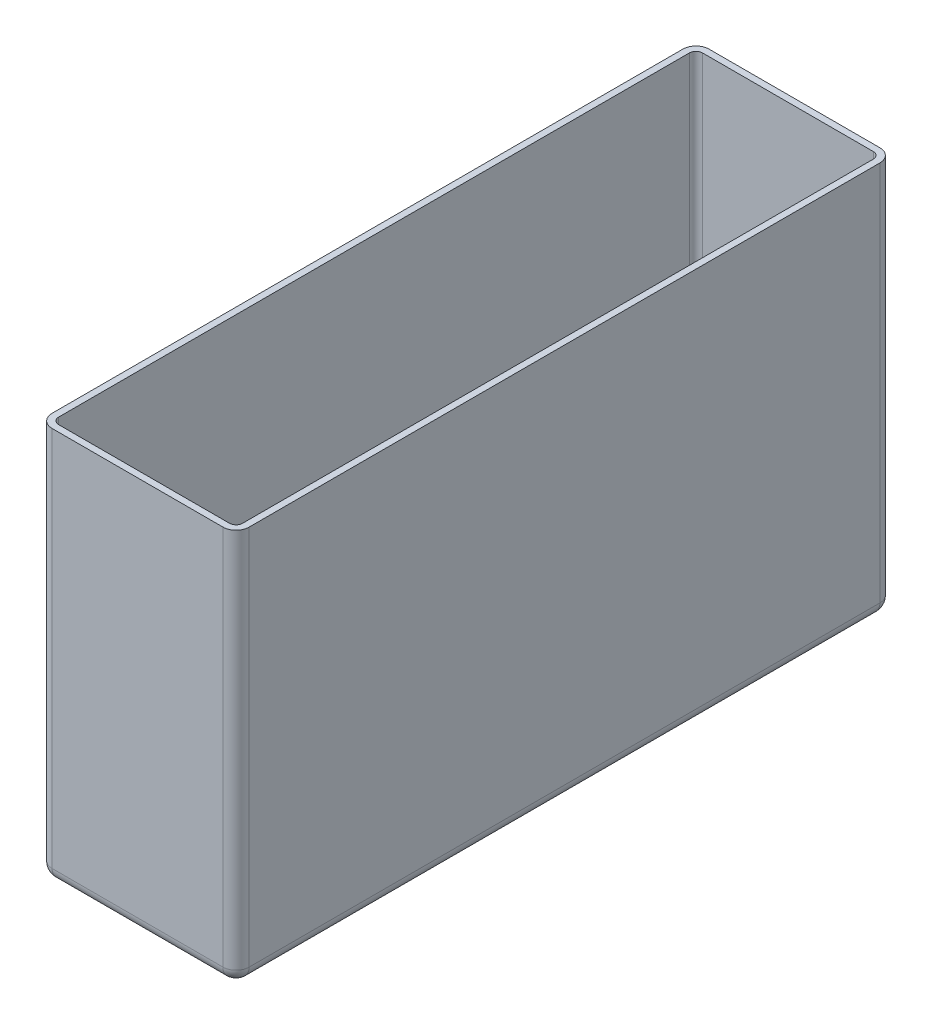
SolidWorks part; units mm, degrees
ref_plane "Alzado" through (0, 0, 0) normal (0, 0, 1) x (1, 0, 0)
ref_plane "Planta" through (0, 0, 0) normal (0, 1, 0) x (1, 0, 0)
ref_plane "Vista lateral" through (0, 0, 0) normal (1, 0, 0) x (0, 0, -1)
sketch "Croquis1" plane through (0, 0, 0) normal (0, 1, 0) x (1, 0, 0)
  line L1 (75, -250) -> (-75, -250)
  line L2 (75, -250) -> (75, 250)
  line L3 (75, 250) -> (-75, 250)
  line L4 (-75, -250) -> (-75, 250)
  line L5 (75, -250) -> (-75, 250) construction
  line L6 (75, 250) -> (-75, -250) construction
  point P0 (0, 0)
  dimension "D1" = 500
  dimension "D2" = 150
extrude "Extruir1" add sketch "Croquis1" along normal blind 300
fillet "Redondeo1" radius 10 8 edges at (0, 0, 250) (75, 0, 0) (0, 0, -250) (-75, 0, 0) (-75, 150, -250) (75, 150, -250) (75, 150, 250) (-75, 150, 250)
shell "Vaciado1" thickness 5
